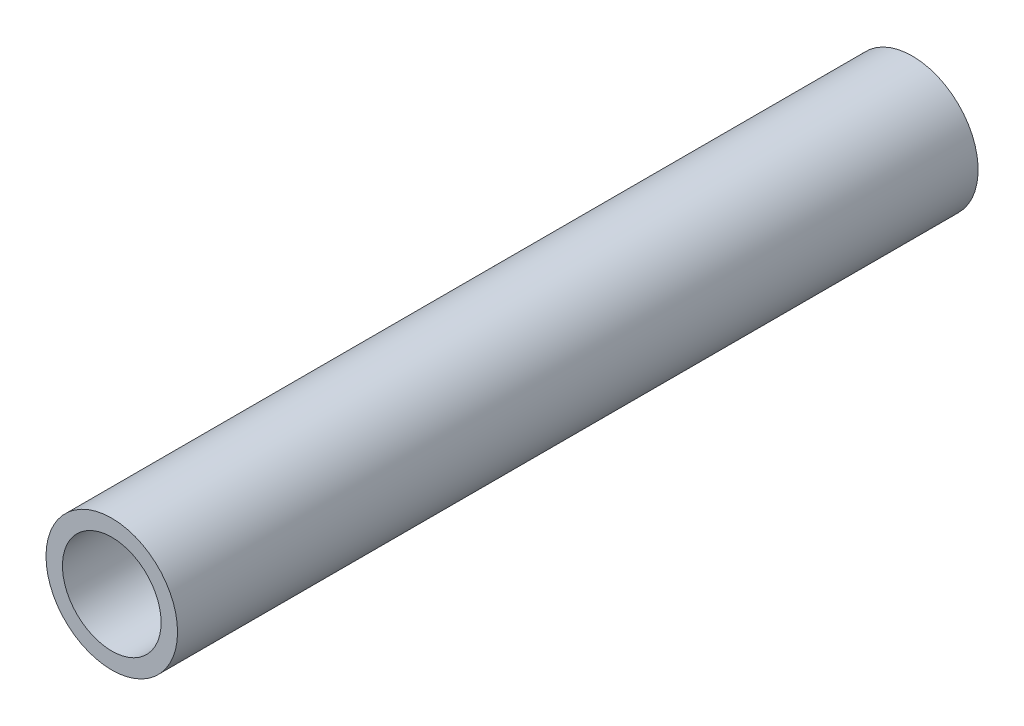
SolidWorks part; units mm, degrees
material "1.7036 (28CrS4)"
ref_plane "정면" through (0, 0, 0) normal (0, 0, 1) x (1, 0, 0)
ref_plane "윗면" through (0, 0, 0) normal (0, 1, 0) x (1, 0, 0)
ref_plane "우측면" through (0, 0, 0) normal (1, 0, 0) x (0, 0, -1)
sketch "스케치1" plane through (0, 0, 0) normal (0, 0, 1) x (1, 0, 0)
  circle A0 centre (0, 0) radius 20
  dimension "D1" = 40
extrude "보스-돌출1" add sketch "스케치1" along normal blind 208.44
sketch "스케치2" plane through (0, 0, 208.44) normal (0, 0, 1) x (1, 0, 0)
  text T0 "TEST\r\n"
sketch "스케치3" plane through (0, 0, 0) normal (0, 0, -1) x (-1, 0, 0)
  circle A0 centre (0, 0) radius 20
extrude "보스-돌출2" add sketch "스케치3" along normal blind 35
sketch "스케치4" plane through (0, 0, -35) normal (0, 0, -1) x (-1, 0, 0)
  line L0 (-3.5157, 3.5553) -> (-3.4843, -3.5861)
  arc A0 (-3.4843, -3.5861) -> (-3.5157, 3.5553) centre (0, 0) ccw
  dimension "D1" = 5
  dimension "D2" = 3.5
  dimension "D3" = 7.1414
extrude "컷-돌출1" cut sketch "스케치4" against normal blind 25
sketch "스케치5" plane through (0, 0, -35) normal (0, 0, -1) x (-1, 0, 0)
  circle A0 centre (0, 0) radius 5
extrude "컷-돌출2" cut sketch "스케치5" against normal blind 10
sketch "스케치6" plane through (0, 0, 208.44) normal (0, 0, 1) x (1, 0, 0)
  circle A0 centre (0, 0) radius 15
  circle A1 centre (0, 0) radius 20 construction
  dimension "D1" = 5
extrude "컷-돌출3" cut sketch "스케치6" against normal blind 200
equation "\"`\"=4"
